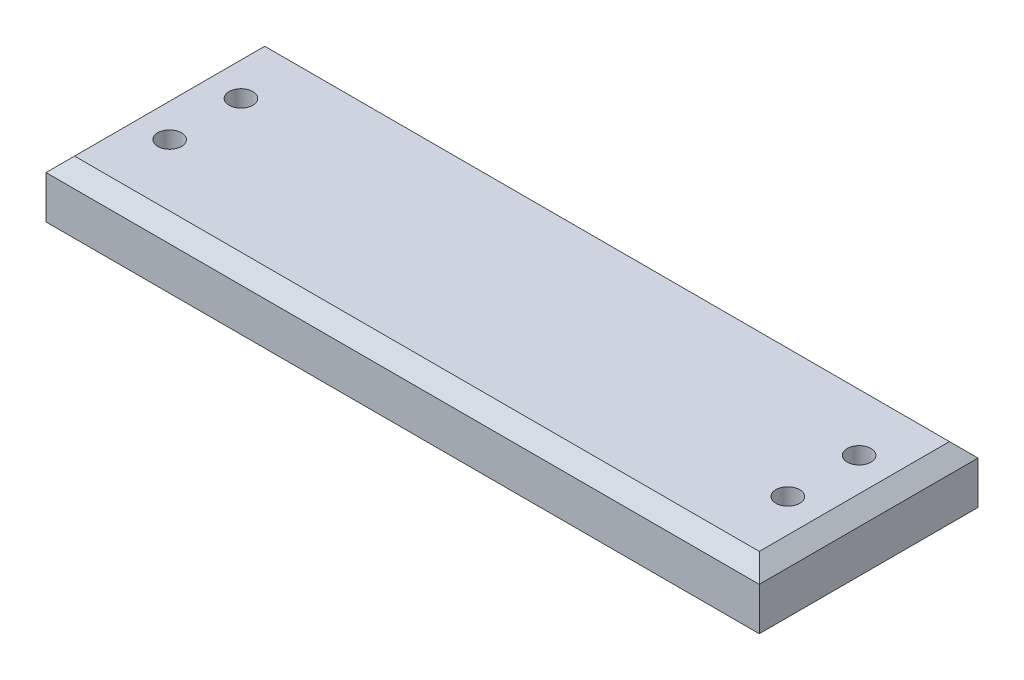
SolidWorks part; units mm, degrees
ref_plane "Front Plane" through (0, 0, 0) normal (0, 0, 1) x (1, 0, 0)
ref_plane "Top Plane" through (0, 0, 0) normal (0, 1, 0) x (1, 0, 0)
ref_plane "Right Plane" through (0, 0, 0) normal (1, 0, 0) x (0, 0, -1)
sketch "Sketch2" plane through (0, 0, 0) normal (0, 1, 0) x (1, 0, 0)
  line L1 (75, 23) -> (-75, 23)
  line L2 (75, 23) -> (75, -23)
  line L3 (75, -23) -> (-75, -23)
  line L4 (-75, 23) -> (-75, -23)
  point P4 (0, 23)
  point P6 (-75, 0)
  dimension "D1" = 46
  dimension "D2" = 150
extrude "Boss-Extrude1" add sketch "Sketch2" along normal mid plane 12
chamfer "Chamfer2" distance 3 angle 45 4 edges at (0, 6, 23) (-75, 6, 0) (0, 6, -23) (75, 6, 0)
sketch "Sketch3" plane through (0, 6, 0) normal (0, 1, 0) x (1, 0, 0)
  line L0 (-65, 8) -> (65, 8) construction
  line L1 (65, 8) -> (65, -7) construction
  line L2 (65, -7) -> (-65, -7) construction
  line L3 (-65, -7) -> (-65, 8) construction
  line L4 (-75, -23) -> (-75, 23) construction
  line L5 (75, -23) -> (-75, -23) construction
  circle A0 centre (-65, 8) radius 2.5
  circle A1 centre (-65, -7) radius 2.5
  circle A2 centre (65, 8) radius 2.5
  circle A3 centre (65, -7) radius 2.5
  point P12 (0, 0)
  dimension "D5" = 5
  dimension "D1" = 10
  dimension "D2" = 140
  dimension "D3" = 16
  dimension "D4" = 31
extrude "Cut-Extrude1" cut sketch "Sketch3" against normal through all contours A0 | A1 | A2 | A3
chamfer "Chamfer3" distance 1.5 angle 45 4 edges at (-65, -6, 9.5) (-65, -6, -5.5) (65, -6, 9.5) (65, -6, -5.5)
